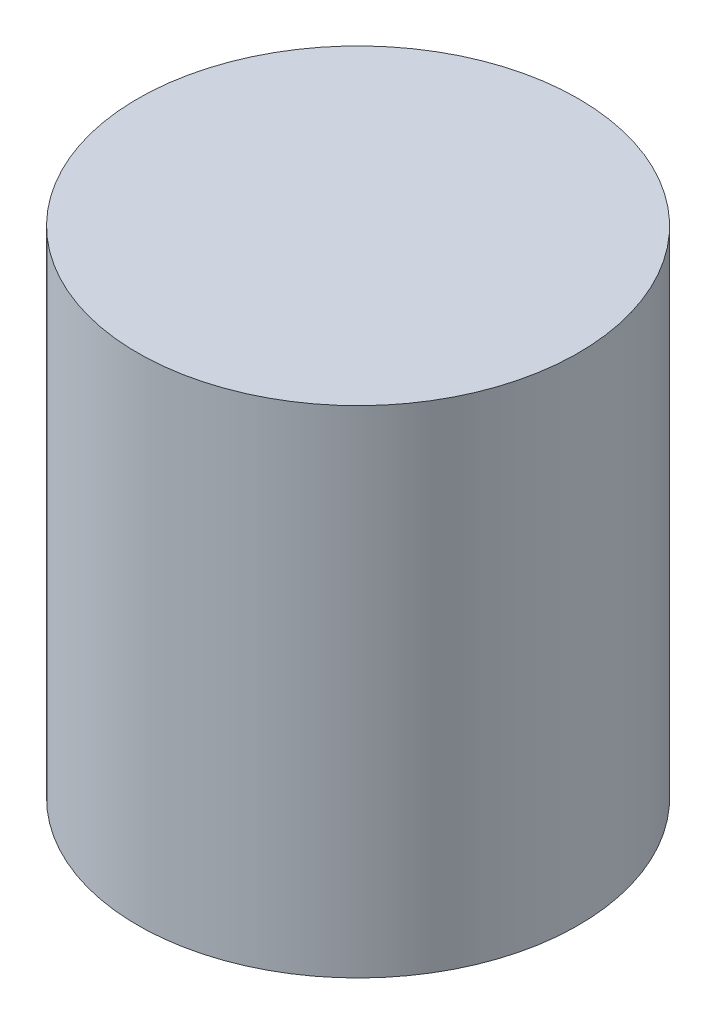
SolidWorks part; units mm, degrees
ref_plane "Front Plane" through (0, 0, 0) normal (0, 0, 1) x (1, 0, 0)
ref_plane "Top Plane" through (0, 0, 0) normal (0, 1, 0) x (1, 0, 0)
ref_plane "Right Plane" through (0, 0, 0) normal (1, 0, 0) x (0, 0, -1)
sketch "Sketch1" plane through (0, 0, 0) normal (0, 1, 0) x (1, 0, 0)
  circle A0 centre (0, 0) radius 20
  dimension "D1" = 40
extrude "Boss-Extrude1" add sketch "Sketch1" along normal mid plane 45
